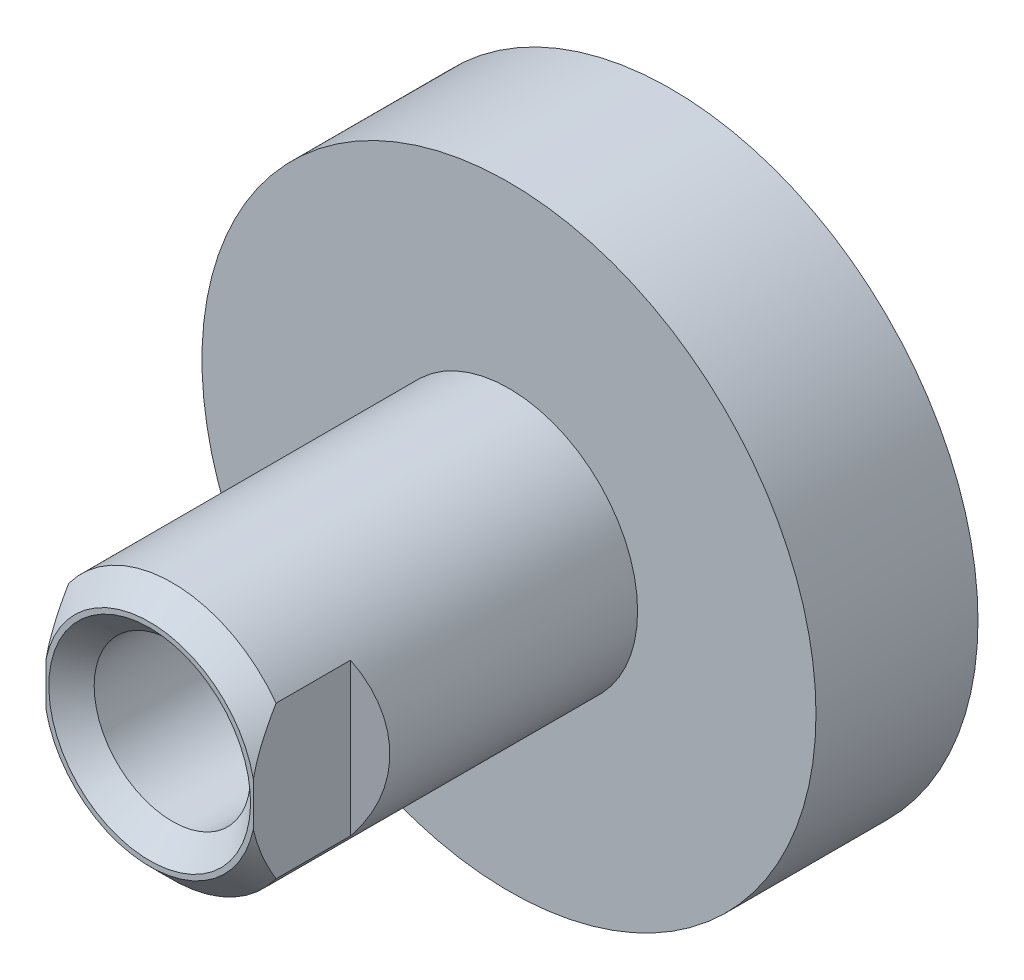
SolidWorks part; units mm, degrees
ref_plane "Front" through (0, 0, 0) normal (0, 0, 1) x (1, 0, 0)
ref_plane "Top" through (0, 0, 0) normal (0, 1, 0) x (1, 0, 0)
ref_plane "Right" through (0, 0, 0) normal (1, 0, 0) x (0, 0, -1)
sketch "Sketch1" plane through (0, 0, 0) normal (0, 0, 1) x (1, 0, 0)
  circle A0 centre (0, 0) radius 9.475
  dimension "D1" = 18.95
extrude "Piston" add sketch "Sketch1" along normal blind 5
sketch "Sketch2" plane through (0, 0, 0) normal (0, 0, -1) x (-1, 0, 0)
  circle A0 centre (0, 0) radius 3.969
  dimension "D1" = 7.938
extrude "Rod" add sketch "Sketch2" against normal up to surface (16.089 mm away)
sketch "Sketch8" plane through (0, 0, 16.089) normal (0, 0, 1) x (1, 0, 0)
  point P0 (0, 0)
hole_wizard "056 #8-32 Internal Thread" [suppressed] positions "3DSketch2" profile "Sketch9" tap size "#8-32" standard "Ansi Inch"
sketch3d "3DSketch2"
  point P0 (0, 0, 68.54)
sketch "Sketch9" plane through (0, 0, 68.54) normal (1, 0, 0) x (0, -1, 0)
  line L0 (0, 0) -> (0, 12.5378)
  line L1 (0, 12.5378) -> (1.7272, 11.5)
  line L2 (1.7272, 11.5) -> (1.7272, 9.144)
  line L3 (1.7272, 9.144) -> (2.0828, 9.144)
  line L4 (2.0828, 9.144) -> (2.0828, 0)
  line L5 (2.0828, 0) -> (0, 0)
  line L10 (0, 12.5378) -> (-1.7272, 11.5) construction
  line L11 (0, -6.35) -> (0, 107.95) construction
  dimension "Tap Drill Dia." = 3.4544
  dimension "Tap Drill Depth" = 11.5
  dimension "Thread Major Dia." = 4.1656
  dimension "Thread Depth" = 9.144
  dimension "Drill Angle" = 118
hole_wizard "075 #10-32 Internal Thread" positions "3DSketch3" profile "Sketch12" tap size "#10-32" standard "Ansi Inch"
sketch3d "3DSketch3"
  point P0 (0, 0, 16.089)
sketch "Sketch12" plane through (0, 0, 16.089) normal (1, 0, 0) x (0, -1, 0)
  line L0 (0, 0) -> (0, 12.7133)
  line L1 (0, 12.7133) -> (2.0193, 11.5)
  line L2 (2.0193, 11.5) -> (2.0193, 9.144)
  line L3 (2.0193, 9.144) -> (2.413, 9.144)
  line L4 (2.413, 9.144) -> (2.413, 0)
  line L5 (2.413, 0) -> (0, 0)
  line L10 (0, 12.7133) -> (-2.0193, 11.5) construction
  line L11 (0, -6.35) -> (0, 107.95) construction
  dimension "Tap Drill Dia." = 4.0386
  dimension "Tap Drill Depth" = 11.5
  dimension "Thread Major Dia." = 4.826
  dimension "Thread Depth" = 9.144
  dimension "Drill Angle" = 118
hole_wizard "106 5/16-24 Internal Thread" [suppressed] positions "3DSketch4" profile "Sketch13" tap size "5/16-24" standard "Ansi Inch"
sketch3d "3DSketch4"
  point P0 (0, 0, 50)
sketch "Sketch13" plane through (0, 0, 50) normal (1, 0, 0) x (0, -1, 0)
  line L0 (0, 0) -> (0, 18.4532)
  line L1 (0, 18.4532) -> (3.4544, 16.3775)
  line L2 (3.4544, 16.3775) -> (3.4544, 13.2)
  line L3 (3.4544, 13.2) -> (3.9687, 13.2)
  line L4 (3.9687, 13.2) -> (3.9687, 0)
  line L5 (3.9687, 0) -> (0, 0)
  line L10 (0, 18.4532) -> (-3.4544, 16.3775) construction
  line L11 (0, -6.35) -> (0, 107.95) construction
  dimension "Tap Drill Dia." = 6.9088
  dimension "Tap Drill Depth" = 16.3775
  dimension "Thread Major Dia." = 7.9375
  dimension "Thread Depth" = 13.208
  dimension "Drill Angle" = 118
hole_wizard "150 3/8-24 Internal Thread" [suppressed] positions "3DSketch5" profile "Sketch14" tap size "3/8-24" standard "Ansi Inch"
sketch3d "3DSketch5"
  point P0 (0, 0, 50)
sketch "Sketch14" plane through (0, 0, 50) normal (1, 0, 0) x (0, -1, 0)
  line L0 (0, 0) -> (0, 18.411)
  line L1 (0, 18.411) -> (4.2164, 15.8775)
  line L2 (4.2164, 15.8775) -> (4.2164, 12.7)
  line L3 (4.2164, 12.7) -> (4.7625, 12.7)
  line L4 (4.7625, 12.7) -> (4.7625, 0)
  line L5 (4.7625, 0) -> (0, 0)
  line L10 (0, 18.411) -> (-4.2164, 15.8775) construction
  line L11 (0, -6.35) -> (0, 107.95) construction
  dimension "Tap Drill Dia." = 8.4328
  dimension "Tap Drill Depth" = 15.8775
  dimension "Thread Major Dia." = 9.525
  dimension "Thread Depth" = 12.7
  dimension "Drill Angle" = 118
hole_wizard "200-250 1/2-20 Internal Thread" [suppressed] positions "3DSketch6" profile "Sketch15" tap size "1/2-20" standard "Ansi Inch"
sketch3d "3DSketch6"
  point P0 (0, 0, 122.515)
sketch "Sketch15" plane through (0, 0, 122.515) normal (1, 0, 0) x (0, -1, 0)
  line L0 (0, 0) -> (0, 23.8576)
  line L1 (0, 23.8576) -> (5.7544, 20.4)
  line L2 (5.7544, 20.4) -> (5.7544, 17.78)
  line L3 (5.7544, 17.78) -> (6.35, 17.78)
  line L4 (6.35, 17.78) -> (6.35, 0)
  line L5 (6.35, 0) -> (0, 0)
  line L10 (0, 23.8576) -> (-5.7544, 20.4) construction
  line L11 (0, -6.35) -> (0, 107.95) construction
  dimension "Tap Drill Dia." = 11.5087
  dimension "Tap Drill Depth" = 15.01
  dimension "Thread Major Dia." = 12.7
  dimension "Thread Depth" = 11.176
  dimension "Drill Angle" = 118
chamfer "Rod End Chamfer" distance 0.7 angle 45 2 edges at (0, 3.969, 16.089) (0, -2.413, 16.089)
sketch "Sketch11" plane through (0, 0, 0) normal (0, 1, 0) x (1, 0, 0)
  line L0 (0, -16.089) -> (0, -54.2319) construction
  line L1 (-3.2, -16.089) -> (-3.2, -13.089)
  line L2 (3.2, -16.089) -> (3.2, -13.089)
  line L3 (-3.2, -13.089) -> (-8.2, -10.2022)
  line L4 (3.2, -13.089) -> (8.2, -10.2022)
  line L5 (-8.2, -10.2022) -> (-8.2, -16.089)
  line L6 (8.2, -10.2022) -> (8.2, -16.089)
  line L7 (-8.2, -16.089) -> (-3.2, -16.089)
  line L8 (8.2, -16.089) -> (3.2, -16.089)
  line L9 (-3.969, -16.089) -> (3.969, -16.089) construction
  dimension "D1" = 60
  dimension "D2" = 5
  dimension "D3" = 3
  dimension "D4" = 6.4
extrude "Wrench Flats" cut sketch "Sketch11" against normal through all and the other way through all
sketch "Sketch16" plane through (0, 0, 16.089) normal (0, 0, 1) x (1, 0, 0)
  circle A0 centre (0, 0) radius 2.0828
  dimension "D1" = 4.1656
extrude "External Thread" [suppressed] add sketch "Sketch16" along normal blind 9.652
chamfer "External Rod Thread Chamfer" [suppressed] distance 0.3 angle 45
hole_wizard "300 5/8-18 Internal Thread" [suppressed] positions "3DSketch7" profile "Sketch17" tap size "5/8-18" standard "Ansi Inch"
sketch3d "3DSketch7"
  arc A0 (7.95, 3.0778, 122.515) -> (-7.95, 3.0778, 122.515) centre (0, 0, 122.515) ccw construction
  point P6 (0, 0, 122.515)
  point P15 (0, 0, 131.04)
sketch "Sketch17" plane through (0, 0, 122.515) normal (1, 0, 0) x (0, -1, 0)
  line L0 (0, 0) -> (0, 19.8164)
  line L1 (0, 19.8164) -> (7.3419, 15.405)
  line L2 (7.3419, 15.405) -> (7.3419, 11.176)
  line L3 (7.3419, 11.176) -> (7.9375, 11.176)
  line L4 (7.9375, 11.176) -> (7.9375, 0)
  line L5 (7.9375, 0) -> (0, 0)
  line L10 (0, 19.8164) -> (-7.3419, 15.405) construction
  line L11 (0, -6.35) -> (0, 107.95) construction
  dimension "Tap Drill Dia." = 14.6837
  dimension "Tap Drill Depth" = 15.405
  dimension "Thread Major Dia." = 15.875
  dimension "Thread Depth" = 11.176
  dimension "Drill Angle" = 118
hole_wizard "400 3/4-16 Internal Thread" [suppressed] positions "3DSketch8" profile "Sketch18" tap size "3/4-16" standard "Ansi Inch"
sketch3d "3DSketch8"
  arc A0 (11.176, 3.4622, 122.515) -> (-11.176, 3.4622, 122.515) centre (0, 0, 122.515) ccw construction
  point P0 (0, 0, 122.515)
  point P9 (0, 0, 134.215)
sketch "Sketch18" plane through (0, 0, 122.515) normal (1, 0, 0) x (0, -1, 0)
  line L0 (0, 0) -> (0, 21.7563)
  line L1 (0, 21.7563) -> (8.7312, 16.51)
  line L2 (8.7312, 16.51) -> (8.7312, 16.448)
  line L3 (8.7312, 16.448) -> (9.525, 16.448)
  line L4 (9.525, 16.448) -> (9.525, 0)
  line L5 (9.525, 0) -> (0, 0)
  line L10 (0, 21.7563) -> (-8.7313, 16.51) construction
  line L11 (0, -6.35) -> (0, 107.95) construction
  dimension "Tap Drill Dia." = 17.4625
  dimension "Tap Drill Depth" = 16.51
  dimension "Thread Major Dia." = 19.05
  dimension "Thread Depth" = 16.448
  dimension "Drill Angle" = 118
